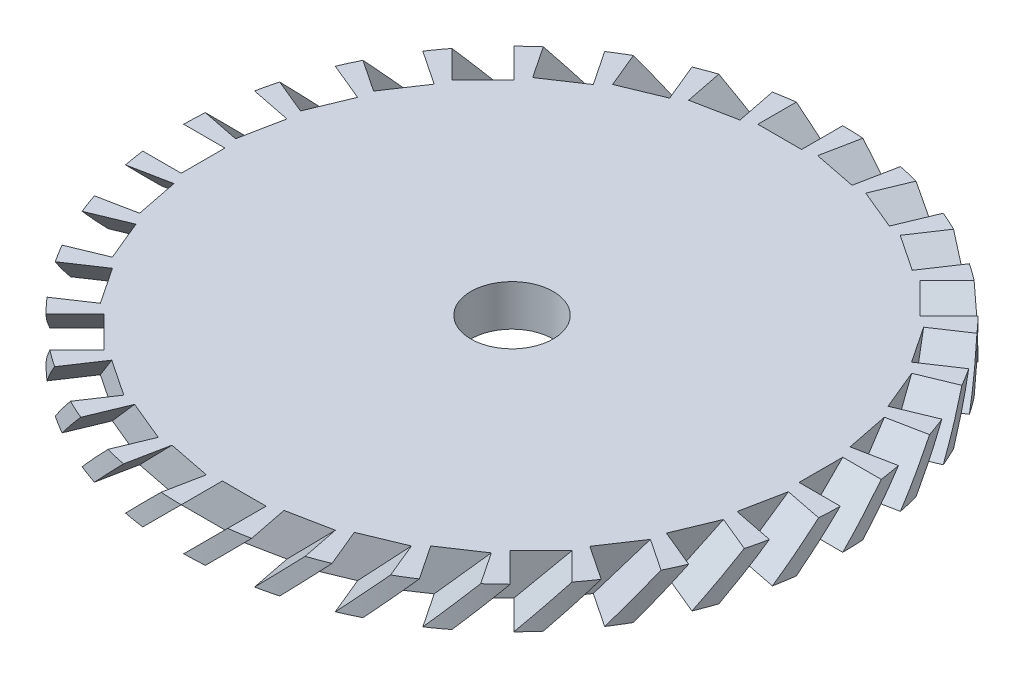
SolidWorks part; units mm, degrees
material "Nickel"
ref_plane "Front Plane" through (0, 0, 0) normal (0, 0, 1) x (1, 0, 0)
ref_plane "Top Plane" through (0, 0, 0) normal (0, 1, 0) x (1, 0, 0)
ref_plane "Right Plane" through (0, 0, 0) normal (1, 0, 0) x (0, 0, -1)
sketch "Sketch1" plane through (0, 0, 0) normal (0, 1, 0) x (1, 0, 0)
  circle A0 centre (0, 0) radius 6.35
  circle A1 centre (0, 0) radius 50.8
  dimension "D1" = 12.7
  dimension "D2" = 101.6
extrude "Boss-Extrude1" add sketch "Sketch1" along normal blind 6.35
ref_plane "Plane1" through (0, 0, 50.8) normal (0, 0, 1) x (1, 0, 0)
sketch "Sketch2" plane through (0, 0, 50.8) normal (0, 0, 1) x (1, 0, 0)
  line L0 (15.1542, 14.9616) -> (-11.7866, -11.9792)
  line L1 (15.1542, 14.9616) -> (11.7866, 18.3292)
  line L2 (-11.7866, -11.9792) -> (-15.1542, -8.6116)
  line L3 (11.7866, 18.3292) -> (-15.1542, -8.6116)
  line L4 (15.1542, 14.9616) -> (-15.1542, -8.6116) construction
  line L5 (-11.7866, -11.9792) -> (11.7866, 18.3292) construction
  line L6 (0, 0) -> (0, 6.35) construction
  line L7 (6.35, 6.35) -> (-6.35, 6.35) construction
  line L8 (-50.8, 0) -> (50.8, 0) construction
  point P1 (0, 3.175)
  dimension "D1" = 45
  dimension "D2" = 4.7625
  dimension "D3" = 38.1
extrude "Cut-Extrude1" cut sketch "Sketch2" against normal blind 6.35
pattern_circular "CirPattern1" count 32 over 360 about axis through (0, 0, 0) along (0, 1, 0) of "Cut-Extrude1"
